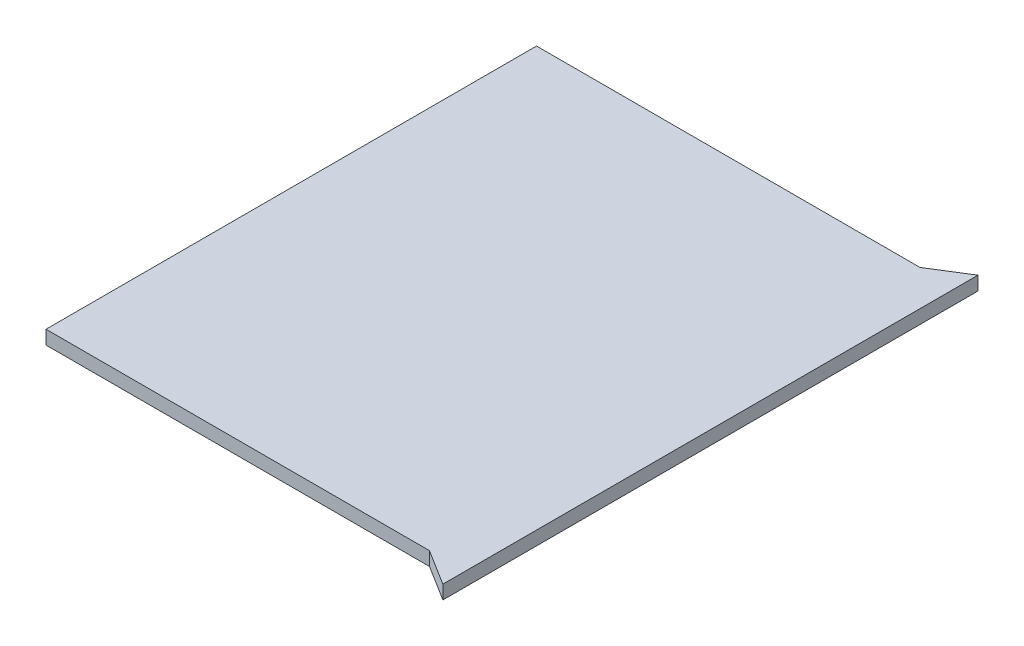
SolidWorks part; units mm, degrees
ref_plane "Front Plane" through (0, 0, 0) normal (0, 0, 1) x (1, 0, 0)
ref_plane "Top Plane" through (0, 0, 0) normal (0, 1, 0) x (1, 0, 0)
ref_plane "Right Plane" through (0, 0, 0) normal (1, 0, 0) x (0, 0, -1)
sketch "Sketch1" plane through (0, 0, 0) normal (0, 1, 0) x (1, 0, 0)
  line L0 (21.5, 0) -> (25.5, 0) construction
  line L1 (-21.5, -27.5) -> (21.5, -27.5)
  line L2 (-21.5, -27.5) -> (-21.5, 27.5)
  line L3 (-21.5, 27.5) -> (21.5, 27.5)
  line L4 (21.5, -27.5) -> (21.5, 27.5) construction
  line L5 (-21.5, -27.5) -> (21.5, 27.5) construction
  line L6 (-21.5, 27.5) -> (21.5, -27.5) construction
  line L7 (25.5, 30) -> (25.5, -30)
  line L8 (21.5, -27.5) -> (25.5, -30)
  line L9 (21.5, 27.5) -> (25.5, 30)
  point P0 (0, 0)
  point P11 (25.5, 0)
  dimension "D1" = 43
  dimension "D2" = 55
  dimension "D3" = 60
  dimension "D4" = 4
extrude "Boss-Extrude2" add sketch "Sketch1" along normal blind 1.54 contours L3 L9 L7 L8 L1 L2
